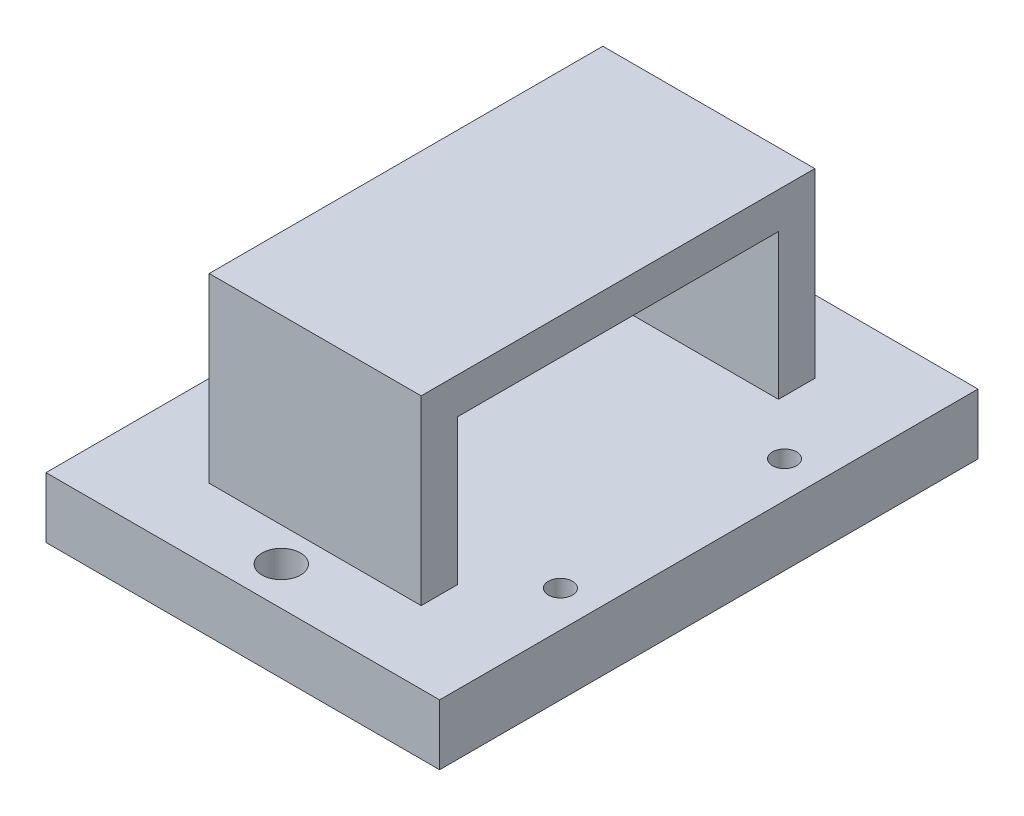
SolidWorks part; units mm, degrees
material "PETG"
ref_plane "Front Plane" through (0, 0, 0) normal (0, 0, 1) x (1, 0, 0)
ref_plane "Top Plane" through (0, 0, 0) normal (0, 1, 0) x (1, 0, 0)
ref_plane "Right Plane" through (0, 0, 0) normal (1, 0, 0) x (0, 0, -1)
sketch "Sketch1" plane through (0, 0, 0) normal (0, 1, 0) x (1, 0, 0)
  line L0 (-26.5, 18.5) -> (26.5, 18.5) construction
  line L1 (-30.25, -21.75) -> (30.25, -21.75)
  line L2 (-30.25, -21.75) -> (-30.25, 21.75)
  line L3 (-30.25, 21.75) -> (30.25, 21.75)
  line L4 (30.25, -21.75) -> (30.25, 21.75)
  line L5 (-30.25, -21.75) -> (30.25, 21.75) construction
  line L6 (-30.25, 21.75) -> (30.25, -21.75) construction
  line L7 (0, 18.5) -> (0, -18.5) construction
  line L8 (-26.5, -18.5) -> (26.5, -18.5) construction
  line L10 (-23, 25.5) -> (23, 25.5)
  line L11 (-23, 25.5) -> (-23, 21.75)
  line L12 (-23, 21.75) -> (23, 21.75)
  line L13 (23, 25.5) -> (23, 21.75)
  line L14 (-23, 25.5) -> (23, 21.75) construction
  line L15 (-23, 21.75) -> (23, 25.5) construction
  line L16 (-23, -21.75) -> (23, -21.75)
  line L17 (-23, -21.75) -> (-23, -25.5)
  line L18 (-23, -25.5) -> (23, -25.5)
  line L19 (23, -21.75) -> (23, -25.5)
  line L20 (-23, -21.75) -> (23, -25.5) construction
  line L21 (-23, -25.5) -> (23, -21.75) construction
  circle A0 centre (-26.5, 18.5) radius 1.75
  circle A1 centre (-26.5, -18.5) radius 1.75
  circle A2 centre (26.5, -18.5) radius 1.75
  circle A3 centre (26.5, 18.5) radius 1.75
  point P0 (0, 0)
  point P23 (0, 23.625)
  point P26 (0, -23.625)
  dimension "D3" = 53
  dimension "D5" = 3.5
  dimension "D1" = 60.5
  dimension "D2" = 43.5
  dimension "D4" = 37
  dimension "D6" = 46
  dimension "D7" = 51
sketch "Sketch2" plane through (0, 0, 0) normal (0, 1, 0) x (1, 0, 0)
  line L1 (-32.5, 32.5) -> (32.5, 32.5)
  line L2 (-32.5, 32.5) -> (-32.5, -32.5)
  line L3 (-32.5, -32.5) -> (32.5, -32.5)
  line L4 (32.5, 32.5) -> (32.5, -32.5)
  line L5 (-32.5, 32.5) -> (32.5, -32.5) construction
  line L6 (-32.5, -32.5) -> (32.5, 32.5) construction
  point P4 (0, 0)
  dimension "D1" = 65
  dimension "D2" = 65
extrude "Boss-Extrude1" add sketch "Sketch2" against normal blind 10
sketch "Sketch3" plane through (0, 0, 0) normal (1, 0, 0) x (0, 0, -1)
  line L0 (32.5, -10) -> (32.5, 0) construction
  line L1 (-32.5, 30) -> (32.5, 30)
  line L2 (-32.5, 30) -> (-32.5, 24)
  line L3 (-32.5, 24) -> (32.5, 24)
  line L4 (32.5, 30) -> (32.5, 24)
  line L5 (-32.5, 0) -> (32.5, 0) construction
  line L6 (-32.5, 24) -> (-26.5, 24)
  line L7 (-32.5, -10) -> (-32.5, 0) construction
  line L8 (-32.5, 24) -> (-32.5, 0)
  line L9 (-32.5, 0) -> (-26.5, 0)
  line L10 (-26.5, 24) -> (-26.5, 0)
  line L12 (32.5, 24) -> (26.5, 24)
  line L13 (32.5, 24) -> (32.5, 0)
  line L14 (32.5, 0) -> (26.5, 0)
  line L15 (26.5, 24) -> (26.5, 0)
  dimension "D1" = 6
  dimension "D2" = 24
extrude "Boss-Extrude2" add sketch "Sketch3" along normal mid plane 35 contours L4 L1 L2 L3 | L3 L15 L14 L13 | L10 L3 L8 L9
sketch "Sketch4" plane through (0, 0, 0) normal (0, 1, 0) x (1, 0, 0)
  line L0 (32.5, -32.5) -> (32.5, 32.5) construction
  line L1 (-32.5, 44.45) -> (32.5, 44.45)
  line L2 (-32.5, 44.45) -> (-32.5, -44.45)
  line L3 (-32.5, -44.45) -> (32.5, -44.45)
  line L4 (32.5, 44.45) -> (32.5, -44.45)
  line L5 (-32.5, 32.5) -> (-32.5, -32.5) construction
  line L6 (0, 44.45) -> (0, -44.45) construction
  line L7 (0, 0) -> (50000, 0) construction
  circle A0 centre (0, 38.1) radius 3.175
  circle A1 centre (0, -38.1) radius 3.175
  point P15 (0, 0)
  dimension "D2" = 6.35
  dimension "D1" = 88.9
  dimension "D3" = 38.1
extrude "Boss-Extrude3" add sketch "Sketch4" against normal up to surface (10 mm away)
sketch "Sketch5" plane through (0, 0, 0) normal (0, 1, 0) x (1, 0, 0)
  circle A0 centre (-26.5, 18.5) radius 1.99
  circle A1 centre (26.5, 18.5) radius 1.99
  circle A2 centre (26.5, -18.5) radius 1.99
  circle A3 centre (-26.5, -18.5) radius 1.99
  dimension "D1" = 3.98
extrude "Cut-Extrude1" cut sketch "Sketch5" against normal through all
equation "\"tol_dia_id_intfc\" = 0.0200mm ' For hole diameters - Interference fit"
equation "\"tol_dia_id_slip\"  = 0.0300mm ' For hole diameters - Slip fit"
equation "\"tol_dia_id_clear\" = 0.0500mm ' For hole diameters - Clearance fit"
equation "\"tol_dia_od_intfc\" = 0.0200mm ' For shaft diameters - Interference fit"
equation "\"tol_dia_od_slip\"  = 0.0300mm ' For shaft diameters - Slip fit"
equation "\"tol_dia_od_clear\" = 0.0500mm ' For shaft diameters - Clearance fit"
equation "\"tol_general_intfc\"= 0.0030mm ' For general parts (Horiz) - Interference fit"
equation "\"tol_general_slip\" = 0.0050mm ' For general parts (Horiz) - Slip fit"
equation "\"tol_general_clear\"= 0.0100mm ' For general parts (Horiz) - Clearance fit"
equation "\"tol_layer_intfc\"  = 0.0030mm ' For all parts (Vert) - Interference fit"
equation "\"tol_layer_slip\"   = 0.0050mm ' For all parts (Vert) - Slip fit"
equation "\"tol_layer_clear\"  = 0.0100mm ' For all parts (Vert) - Clearance fit"
equation "\"tol_corner_rad\"   = 0.100mm ' For corners that fit into other parts"
equation "\"D1@Sketch5\"=3.95+\"tol_dia_id_slip\""
